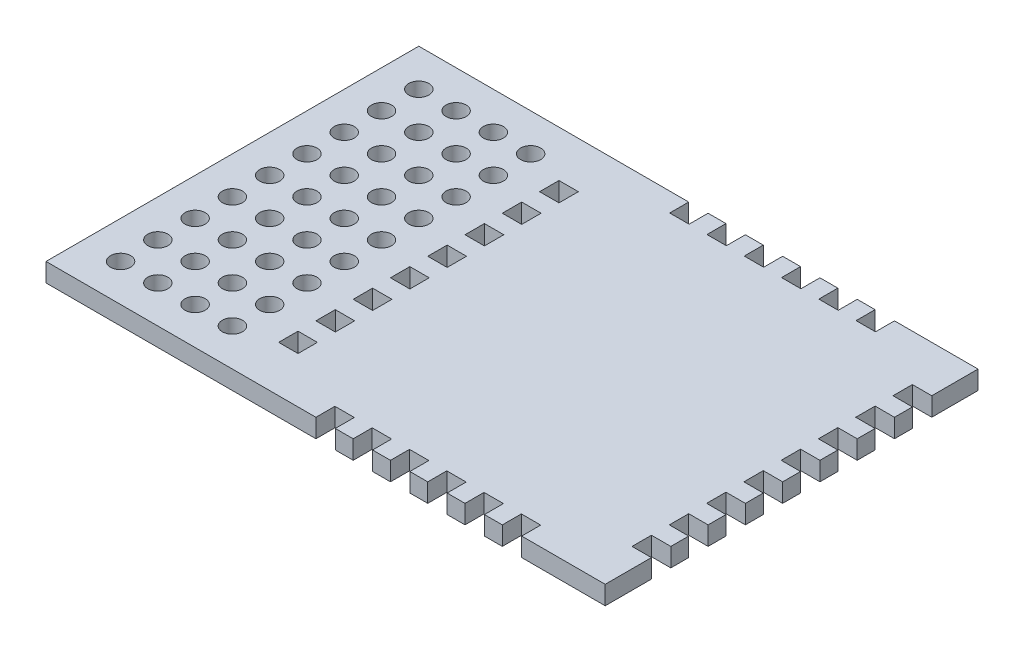
SolidWorks part; units mm, degrees
ref_plane "Front Plane" through (0, 0, 0) normal (0, 0, 1) x (1, 0, 0)
ref_plane "Top Plane" through (0, 0, 0) normal (0, 1, 0) x (1, 0, 0)
ref_plane "Right Plane" through (0, 0, 0) normal (1, 0, 0) x (0, 0, -1)
sketch "Sketch1" plane through (0, 0, 0) normal (0, 1, 0) x (1, 0, 0)
  line L1 (-63.5, -63.5) -> (63.5, -63.5)
  line L2 (-63.5, -63.5) -> (-63.5, 63.5)
  line L3 (-63.5, 63.5) -> (63.5, 63.5)
  line L4 (63.5, -63.5) -> (63.5, 63.5)
  line L5 (-63.5, -63.5) -> (63.5, 63.5) construction
  line L6 (-63.5, 63.5) -> (63.5, -63.5) construction
  line L11 (-41.275, -53.975) -> (41.275, 53.975) construction
  line L12 (-41.275, 53.975) -> (41.275, -53.975) construction
  point P0 (0, 0)
  point P5 (0, 0)
  dimension "D1" = 127
  dimension "D2" = 127
extrude "Boss-Extrude1" add sketch "Sketch1" along normal blind 6.35
sketch "Sketch2" plane through (0, 6.35, 0) normal (0, 1, 0) x (1, 0, 0)
  line L0 (-63.5, -63.5) -> (63.5, -63.5) construction
  line L1 (-35.052, -63.5) -> (-28.448, -63.5)
  line L2 (-35.052, -63.5) -> (-35.052, -57.023)
  line L3 (-35.052, -57.023) -> (-28.448, -57.023)
  line L4 (-28.448, -63.5) -> (-28.448, -57.023)
  line L5 (-22.352, -63.5) -> (-22.352, -57.023)
  line L6 (-22.352, -63.5) -> (-15.748, -63.5)
  line L7 (-15.748, -63.5) -> (-15.748, -57.023)
  line L8 (-22.352, -57.023) -> (-15.748, -57.023)
  line L9 (-9.652, -63.5) -> (-9.652, -57.023)
  line L10 (-9.652, -63.5) -> (-3.048, -63.5)
  line L11 (-3.048, -63.5) -> (-3.048, -57.023)
  line L12 (-9.652, -57.023) -> (-3.048, -57.023)
  line L13 (3.048, -63.5) -> (3.048, -57.023)
  line L14 (3.048, -63.5) -> (9.652, -63.5)
  line L15 (9.652, -63.5) -> (9.652, -57.023)
  line L16 (3.048, -57.023) -> (9.652, -57.023)
  line L17 (15.748, -63.5) -> (15.748, -57.023)
  line L18 (15.748, -63.5) -> (22.352, -63.5)
  line L19 (22.352, -63.5) -> (22.352, -57.023)
  line L20 (15.748, -57.023) -> (22.352, -57.023)
  line L21 (28.448, -63.5) -> (28.448, -57.023)
  line L22 (28.448, -63.5) -> (35.052, -63.5)
  line L23 (35.052, -63.5) -> (35.052, -57.023)
  line L24 (28.448, -57.023) -> (35.052, -57.023)
  line L25 (0, 0) -> (9.652, 0) construction
  line L26 (28.448, 57.023) -> (35.052, 57.023)
  line L27 (35.052, 63.5) -> (35.052, 57.023)
  line L28 (28.448, 63.5) -> (35.052, 63.5)
  line L29 (28.448, 63.5) -> (28.448, 57.023)
  line L30 (15.748, 57.023) -> (22.352, 57.023)
  line L31 (22.352, 63.5) -> (22.352, 57.023)
  line L32 (15.748, 63.5) -> (22.352, 63.5)
  line L33 (15.748, 63.5) -> (15.748, 57.023)
  line L34 (3.048, 57.023) -> (9.652, 57.023)
  line L35 (9.652, 63.5) -> (9.652, 57.023)
  line L36 (3.048, 63.5) -> (9.652, 63.5)
  line L37 (3.048, 63.5) -> (3.048, 57.023)
  line L38 (-9.652, 57.023) -> (-3.048, 57.023)
  line L39 (-3.048, 63.5) -> (-3.048, 57.023)
  line L40 (-9.652, 63.5) -> (-3.048, 63.5)
  line L41 (-9.652, 63.5) -> (-9.652, 57.023)
  line L42 (-22.352, 57.023) -> (-15.748, 57.023)
  line L43 (-15.748, 63.5) -> (-15.748, 57.023)
  line L44 (-22.352, 63.5) -> (-15.748, 63.5)
  line L45 (-22.352, 63.5) -> (-22.352, 57.023)
  line L46 (-28.448, 63.5) -> (-28.448, 57.023)
  line L47 (-35.052, 57.023) -> (-28.448, 57.023)
  line L48 (-35.052, 63.5) -> (-35.052, 57.023)
  line L49 (-35.052, 63.5) -> (-28.448, 63.5)
  line L50 (-63.5, 63.5) -> (-63.5, -63.5) construction
  line L51 (-63.5, 28.448) -> (-56.896, 28.448)
  line L52 (-63.5, 28.448) -> (-63.5, 35.052)
  line L53 (-63.5, 35.052) -> (-56.896, 35.052)
  line L54 (-56.896, 28.448) -> (-56.896, 35.052)
  line L55 (63.5, 63.5) -> (-63.5, 63.5) construction
  line L56 (-63.5, 15.748) -> (-56.896, 15.748)
  line L57 (-63.5, 15.748) -> (-63.5, 22.352)
  line L58 (-63.5, 22.352) -> (-56.896, 22.352)
  line L59 (-56.896, 15.748) -> (-56.896, 22.352)
  line L60 (-63.5, 3.048) -> (-56.896, 3.048)
  line L61 (-63.5, 3.048) -> (-63.5, 9.652)
  line L62 (-63.5, 9.652) -> (-56.896, 9.652)
  line L63 (-56.896, 3.048) -> (-56.896, 9.652)
  line L64 (-63.5, -9.652) -> (-56.896, -9.652)
  line L65 (-63.5, -9.652) -> (-63.5, -3.048)
  line L66 (-63.5, -3.048) -> (-56.896, -3.048)
  line L67 (-56.896, -9.652) -> (-56.896, -3.048)
  line L68 (-63.5, -22.352) -> (-56.896, -22.352)
  line L69 (-63.5, -22.352) -> (-63.5, -15.748)
  line L70 (-63.5, -15.748) -> (-56.896, -15.748)
  line L71 (-56.896, -22.352) -> (-56.896, -15.748)
  line L72 (-63.5, -35.052) -> (-56.896, -35.052)
  line L73 (-63.5, -35.052) -> (-63.5, -28.448)
  line L74 (-63.5, -28.448) -> (-56.896, -28.448)
  line L75 (-56.896, -35.052) -> (-56.896, -28.448)
  line L84 (0, 0) -> (0, 15.748) construction
  line L93 (56.896, -35.052) -> (56.896, -28.448)
  line L94 (63.5, -28.448) -> (56.896, -28.448)
  line L95 (63.5, -35.052) -> (63.5, -28.448)
  line L96 (63.5, -35.052) -> (56.896, -35.052)
  line L97 (56.896, -22.352) -> (56.896, -15.748)
  line L98 (63.5, -15.748) -> (56.896, -15.748)
  line L99 (63.5, -22.352) -> (63.5, -15.748)
  line L100 (63.5, -22.352) -> (56.896, -22.352)
  line L101 (56.896, -9.652) -> (56.896, -3.048)
  line L102 (63.5, -3.048) -> (56.896, -3.048)
  line L103 (63.5, -9.652) -> (63.5, -3.048)
  line L104 (63.5, -9.652) -> (56.896, -9.652)
  line L105 (56.896, 3.048) -> (56.896, 9.652)
  line L106 (63.5, 9.652) -> (56.896, 9.652)
  line L107 (63.5, 3.048) -> (63.5, 9.652)
  line L108 (63.5, 3.048) -> (56.896, 3.048)
  line L109 (56.896, 15.748) -> (56.896, 22.352)
  line L110 (63.5, 22.352) -> (56.896, 22.352)
  line L111 (63.5, 15.748) -> (63.5, 22.352)
  line L112 (63.5, 15.748) -> (56.896, 15.748)
  line L113 (56.896, 28.448) -> (56.896, 35.052)
  line L114 (63.5, 35.052) -> (56.896, 35.052)
  line L115 (63.5, 28.448) -> (63.5, 35.052)
  line L116 (63.5, 28.448) -> (56.896, 28.448)
  line L117 (-63.5, -47.752) -> (-56.896, -47.752) [skipped]
  line L118 (-63.5, -47.752) -> (-63.5, -41.148) [skipped]
  line L119 (-63.5, -41.148) -> (-56.896, -41.148) [skipped]
  line L120 (-56.896, -47.752) -> (-56.896, -41.148) [skipped]
  line L121 (-63.5, -60.452) -> (-56.896, -60.452) [skipped]
  line L122 (-63.5, -60.452) -> (-63.5, -53.848) [skipped]
  line L123 (-63.5, -53.848) -> (-56.896, -53.848) [skipped]
  line L124 (-56.896, -60.452) -> (-56.896, -53.848) [skipped]
  line L125 (-63.5, 41.148) -> (-56.896, 41.148)
  line L126 (-63.5, 41.148) -> (-63.5, 47.752)
  line L127 (-63.5, 47.752) -> (-56.896, 47.752)
  line L128 (-56.896, 41.148) -> (-56.896, 47.752)
  line L129 (-63.5, -47.752) -> (-56.896, -47.752)
  line L130 (-63.5, -47.752) -> (-63.5, -41.148)
  line L131 (-63.5, -41.148) -> (-56.896, -41.148)
  line L132 (-56.896, -47.752) -> (-56.896, -41.148)
  line L133 (56.896, -47.752) -> (56.896, -41.148)
  line L134 (63.5, -41.148) -> (56.896, -41.148)
  line L135 (63.5, -47.752) -> (63.5, -41.148)
  line L136 (63.5, -47.752) -> (56.896, -47.752)
  line L137 (56.896, 41.148) -> (56.896, 47.752)
  line L138 (63.5, 47.752) -> (56.896, 47.752)
  line L139 (63.5, 41.148) -> (63.5, 47.752)
  line L140 (63.5, 41.148) -> (56.896, 41.148)
  line L141 (-35.052, 57.023) -> (-63.5, 57.023) construction
  line L142 (35.052, 57.023) -> (63.5, 57.023) construction
  line L143 (63.5, -63.5) -> (63.5, 63.5) construction
  point P65 (-63.5, 31.75)
  dimension "D1" = 6.604
  dimension "D2" = 6.477
  dimension "D3" = 6.604
  dimension "D5" = 2
  dimension "D6" = 31.75
  dimension "D8" = 12.7
  dimension "D9" = 2
  dimension "D10" = 6.604
  dimension "D13" = 12.7
  dimension "D4" = 6
  dimension "D7" = 8
  dimension "D11" = 2
  dimension "D12" = 2
extrude "Cut-Extrude1" cut sketch "Sketch2" against normal through all
sketch "Sketch3" plane through (0, 6.35, 0) normal (0, 1, 0) x (1, 0, 0)
  line L1 (-63.5, 63.5) -> (-127, 63.5)
  line L2 (-63.5, 63.5) -> (-63.5, -63.5)
  line L3 (-63.5, -63.5) -> (-127, -63.5)
  line L4 (-127, 63.5) -> (-127, -63.5)
  line L5 (-63.5, -63.5) -> (-35.052, -63.5) construction
  circle A0 centre (-114.3, 50.8) radius 3.429
  circle A1 centre (-101.6, 50.8) radius 3.429
  circle A2 centre (-101.6, 38.1) radius 3.429
  circle A6 centre (-114.3, 38.1) radius 3.429
  circle A10 centre (-114.3, 25.4) radius 3.429
  circle A11 centre (-101.6, 25.4) radius 3.429
  circle A12 centre (-88.9, 50.8) radius 3.429
  circle A13 centre (-76.2, 50.8) radius 3.429
  circle A14 centre (-88.9, 38.1) radius 3.429
  circle A15 centre (-76.2, 38.1) radius 3.429
  circle A16 centre (-88.9, 25.4) radius 3.429
  circle A17 centre (-76.2, 25.4) radius 3.429
  circle A18 centre (-114.3, 12.7) radius 3.429
  circle A19 centre (-101.6, 12.7) radius 3.429
  circle A20 centre (-88.9, 12.7) radius 3.429
  circle A21 centre (-76.2, 12.7) radius 3.429
  circle A22 centre (-114.3, 0) radius 3.429
  circle A23 centre (-101.6, 0) radius 3.429
  circle A24 centre (-88.9, 0) radius 3.429
  circle A25 centre (-76.2, 0) radius 3.429
  circle A26 centre (-114.3, -12.7) radius 3.429
  circle A27 centre (-101.6, -12.7) radius 3.429
  circle A28 centre (-88.9, -12.7) radius 3.429
  circle A29 centre (-76.2, -12.7) radius 3.429
  circle A30 centre (-114.3, -25.4) radius 3.429
  circle A31 centre (-101.6, -25.4) radius 3.429
  circle A32 centre (-88.9, -25.4) radius 3.429
  circle A33 centre (-76.2, -25.4) radius 3.429
  circle A34 centre (-114.3, -38.1) radius 3.429
  circle A35 centre (-101.6, -38.1) radius 3.429
  circle A36 centre (-88.9, -38.1) radius 3.429
  circle A37 centre (-76.2, -38.1) radius 3.429
  circle A38 centre (-114.3, -50.8) radius 3.429
  circle A39 centre (-101.6, -50.8) radius 3.429
  circle A40 centre (-88.9, -50.8) radius 3.429
  circle A41 centre (-76.2, -50.8) radius 3.429
  dimension "D2" = 6.858
  dimension "D4" = 12.7
  dimension "D1" = 63.5
  dimension "D3" = 38.1
  dimension "D7" = 12.7
  dimension "D8" = 12.7
  dimension "D5" = 4
  dimension "D6" = 9
extrude "Boss-Extrude2" add sketch "Sketch3" against normal blind 6.35
